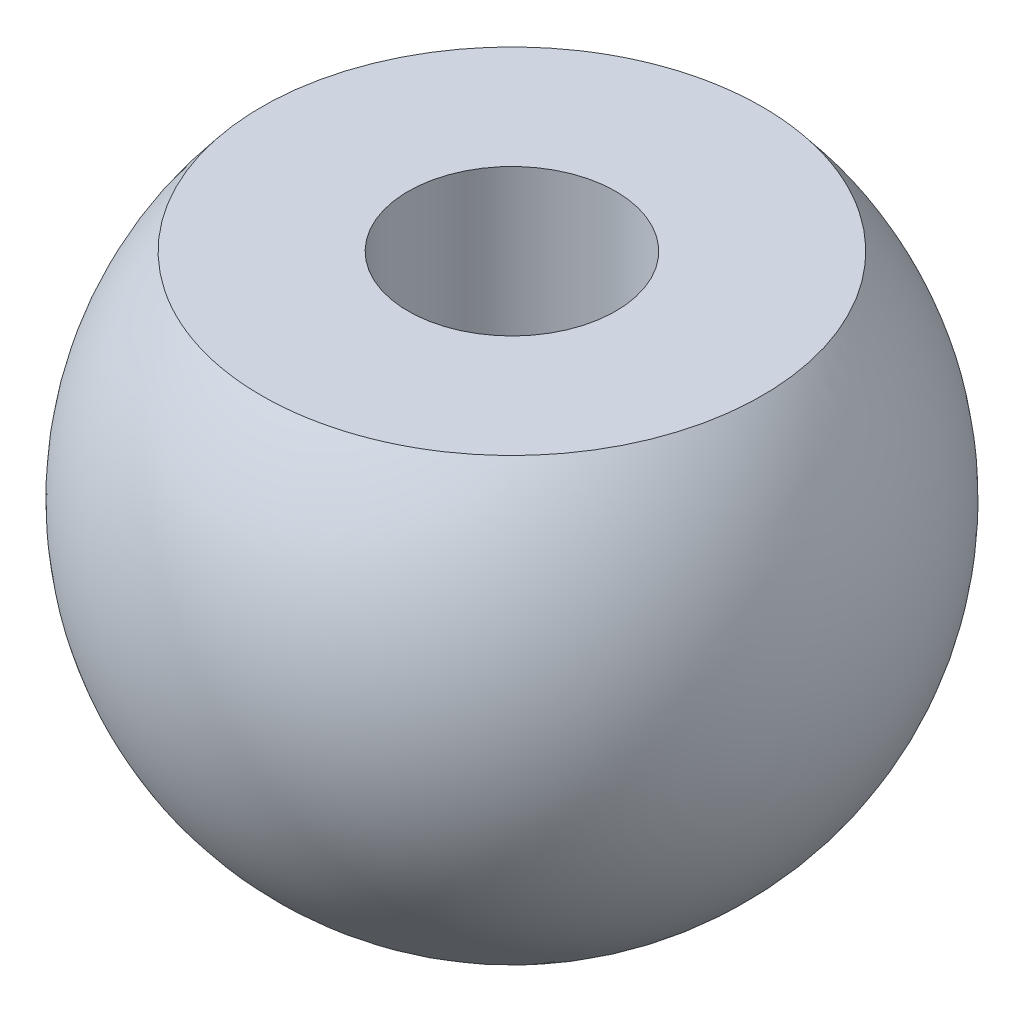
SolidWorks part; units mm, degrees
ref_plane "Front Plane" through (0, 0, 0) normal (0, 0, 1) x (1, 0, 0)
ref_plane "Top Plane" through (0, 0, 0) normal (0, 1, 0) x (1, 0, 0)
ref_plane "Right Plane" through (0, 0, 0) normal (1, 0, 0) x (0, 0, -1)
sketch "Sketch1" plane through (0, 0, 0) normal (0, 1, 0) x (1, 0, 0)
  line L0 (0, 10) -> (0, -10)
  arc A0 (0, -10) -> (0, 10) centre (0, 0) ccw
  dimension "D1" = 20
revolve "Revolve1" add sketch "Sketch1" angle 360 about L0
sketch "Sketch2" plane through (0, 0, 0) normal (0, 1, 0) x (1, 0, 0)
  circle A0 centre (0, 0) radius 3.15
  dimension "D1" = 6.3
extrude "Cut-Extrude1" cut sketch "Sketch2" against normal through all both and the other way through all
ref_plane "Plane1" through (0, -9.4909, 0) normal (0, -1, 0) x (-1, 0, 0)
sketch "Sketch3" plane through (0, -9.4909, 0) normal (0, -1, 0) x (-1, 0, 0)
  line L1 (0.2873, -5.9109) -> (5.2626, -2.7066)
  line L2 (5.2626, -2.7066) -> (4.9753, 3.2043)
  line L3 (4.9753, 3.2043) -> (-0.2873, 5.9109)
  line L4 (-0.2873, 5.9109) -> (-5.2626, 2.7066)
  line L5 (-5.2626, 2.7066) -> (-4.9753, -3.2043)
  line L6 (-4.9753, -3.2043) -> (0.2873, -5.9109)
  circle A0 centre (0, 0) radius 5.125 construction
  dimension "D1" = 10.25
extrude "Cut-Extrude2" cut sketch "Sketch3" against normal blind 5
sketch "Sketch4" plane through (0, -9.4909, 0) normal (0, -1, 0) x (-1, 0, 0)
  circle A0 centre (0, 0) radius 8
  circle A1 centre (0, 0) radius 3.15
  dimension "D1" = 16
extrude "Cut-Extrude3" cut sketch "Sketch4" along normal blind 4 from offset 20
